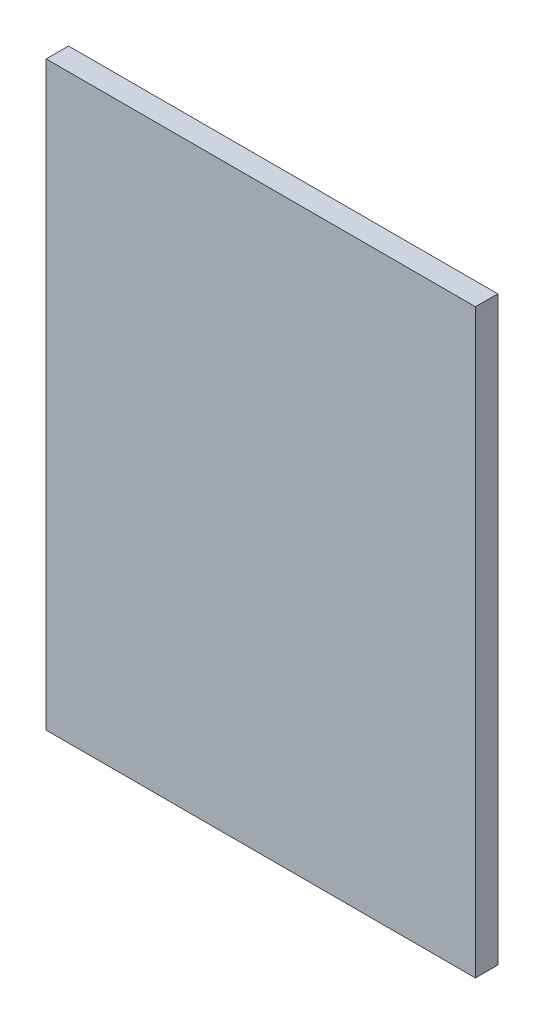
SolidWorks part; units mm, degrees
material "1060 Alloy"
ref_plane "Front Plane" through (0, 0, 0) normal (0, 0, 1) x (1, 0, 0)
ref_plane "Top Plane" through (0, 0, 0) normal (0, 1, 0) x (1, 0, 0)
ref_plane "Right Plane" through (0, 0, 0) normal (1, 0, 0) x (0, 0, -1)
sketch "Sketch1" plane through (0, 0, 0) normal (0, 0, 1) x (1, 0, 0)
  line L1 (-29.4866, 51.6858) -> (66.5134, 51.6858)
  line L2 (-29.4866, 51.6858) -> (-29.4866, -78.3142)
  line L3 (-29.4866, -78.3142) -> (66.5134, -78.3142)
  line L4 (66.5134, 51.6858) -> (66.5134, -78.3142)
  dimension "D1" = 130
  dimension "D2" = 96
extrude "Boss-Extrude1" add sketch "Sketch1" along normal blind 5
